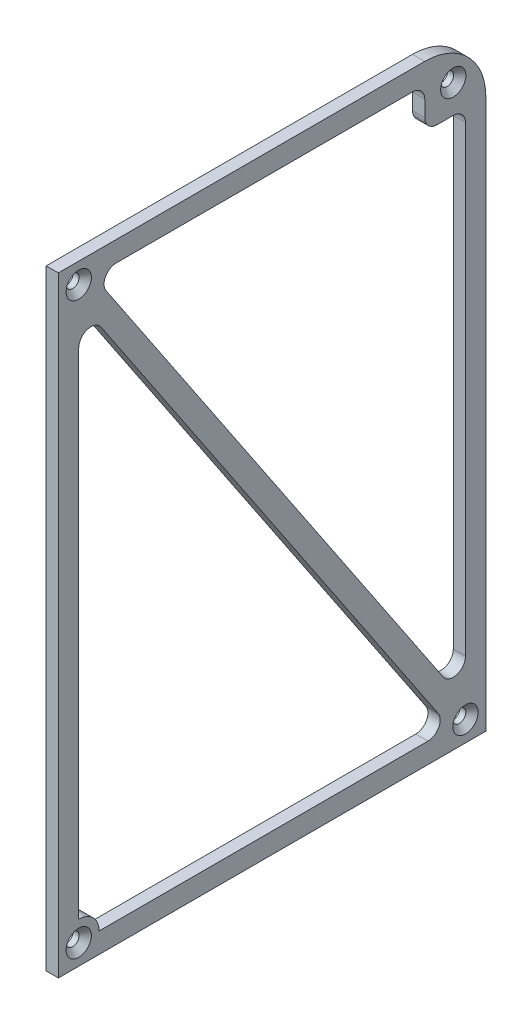
SolidWorks part; units mm, degrees
ref_plane "Front Plane" through (0, 0, 0) normal (0, 0, 1) x (1, 0, 0)
ref_plane "Top Plane" through (0, 0, 0) normal (0, 1, 0) x (1, 0, 0)
ref_plane "Right Plane" through (0, 0, 0) normal (1, 0, 0) x (0, 0, -1)
sketch "Sketch1" plane through (0, 0, 0) normal (1, 0, 0) x (0, 0, -1)
  line L0 (5, 5) -> (5, 6.6)
  line L1 (0, 0) -> (105, 0)
  line L2 (0, 0) -> (0, 150)
  line L3 (0, 150) -> (90, 150)
  line L4 (105, 0) -> (105, 135)
  line L5 (5, 145) -> (6.6, 145)
  line L6 (100, 5) -> (100, 6.6)
  line L7 (5, 5) -> (6.6, 5)
  line L8 (8.6, 145) -> (90, 145)
  line L9 (5, 143.4) -> (5, 145)
  line L10 (5, 145) -> (90, 145) construction
  line L11 (5, 10) -> (5, 141.4)
  line L12 (5, 5) -> (5, 145) construction
  line L13 (10, 5) -> (96.4, 5)
  line L14 (98.4, 5) -> (100, 5)
  line L15 (5, 5) -> (100, 5) construction
  line L16 (100, 8.6) -> (100, 135)
  line L17 (0, 150) -> (131.8816, 150) construction
  line L18 (100, 5) -> (100, 135) construction
  line L19 (105, 0) -> (105, 197.6676) construction
  line L20 (5, 141.4) -> (96.4, 5)
  line L21 (100, 8.6) -> (8.6, 145)
  line L22 (90, 135) -> (117.2655, 135) construction
  line L23 (90, 135) -> (109.727, 154.727) construction
  line L24 (90, 145) -> (90, 135)
  line L25 (90, 135) -> (100, 135)
  circle A0 centre (5, 145) radius 1.6
  circle A1 centre (97, 142) radius 1.6
  circle A2 centre (100, 5) radius 1.6
  circle A3 centre (5, 5) radius 1.6
  arc A4 (90, 150) -> (105, 135) centre (90, 135) cw
  arc A5 (90, 145) -> (100, 135) centre (90, 135) cw construction
  arc A7 (10, 5) -> (5, 10) centre (5, 5) ccw
  dimension "D3" = 15
  dimension "D5" = 3.2
  dimension "D6" = 3.2
  dimension "D7" = 3.2
  dimension "D8" = 3.2
  dimension "D1" = 105
  dimension "D2" = 150
  dimension "D9" = 5
  dimension "D10" = 5
  dimension "D11" = 5
  dimension "D12" = 5
  dimension "D13" = 5
  dimension "D14" = 5
  dimension "D15" = 2
  dimension "D16" = 2
  dimension "D17" = 2
  dimension "D18" = 2
  dimension "D19" = 45
  dimension "D20" = 8
  dimension "D4" = 5
extrude "Boss-Extrude2" add sketch "Sketch1" along normal blind 3 contours A4 L3 L2 L1 L4 L5 A5 L6 A2 L7 A3 L0
fillet "Fillet1" radius 3 7 edges at (1.5, 8.6, -100) (1.5, 5, -96.4) (1.5, 141.4, -5) (1.5, 145, -8.6) (1.5, 135, -100) (1.5, 135, -90) (1.5, 145, -90)
chamfer "Chamfer1" distance 1.5 angle 45 4 edges at (3, 5, -101.6) (3, 5, -6.6) (3, 142, -98.6) (3, 145, -6.6)
